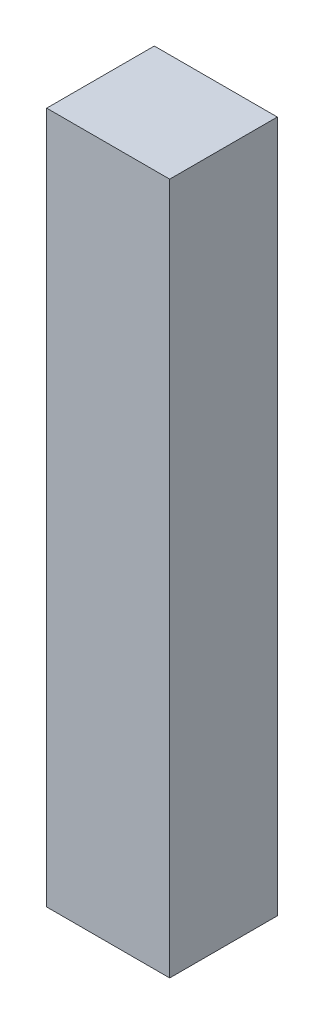
SolidWorks part; units mm, degrees
ref_plane "Front Plane" through (0, 0, 0) normal (0, 0, 1) x (1, 0, 0)
ref_plane "Top Plane" through (0, 0, 0) normal (0, 1, 0) x (1, 0, 0)
ref_plane "Right Plane" through (0, 0, 0) normal (1, 0, 0) x (0, 0, -1)
sketch "Sketch1" plane through (0, 0, 0) normal (0, 1, 0) x (1, 0, 0)
  line L1 (0, 0) -> (8, 0)
  line L2 (0, 0) -> (0, 7)
  line L3 (0, 7) -> (8, 7)
  line L4 (8, 0) -> (8, 7)
  dimension "D1" = 7
  dimension "D2" = 8
extrude "Boss-Extrude1" add sketch "Sketch1" along normal blind 45
